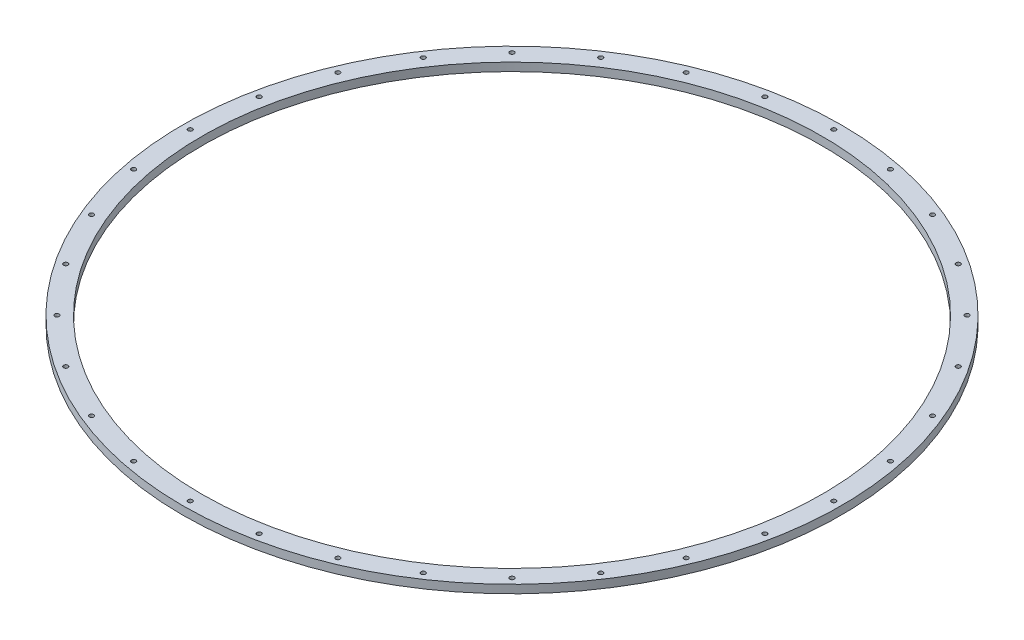
SolidWorks part; units mm, degrees
material "AISI 304"
ref_plane "Front" through (0, 0, 0) normal (0, 0, 1) x (1, 0, 0)
ref_plane "Top" through (0, 0, 0) normal (0, 1, 0) x (1, 0, 0)
ref_plane "Right" through (0, 0, 0) normal (1, 0, 0) x (0, 0, -1)
sketch "Sketch1" plane through (0, 0, 0) normal (0, 1, 0) x (1, 0, 0)
  circle A0 centre (0, 0) radius 239
  circle A1 centre (0, 0) radius 254
  dimension "D1" = 508
  dimension "D2" = 478
extrude "Boss-Extrude1" add sketch "Sketch1" along normal mid plane 6.35
hole_wizard "M3 Clearance Hole1" positions "Sketch2" profile "Sketch3" hole size "M3" standard "ANSI Metric" end condition up to next
sketch "Sketch2" plane through (0, 3.175, 0) normal (0, 1, 0) x (1, 0, 0)
  line L3 (-248, 0) -> (248, 0) construction
  point P0 (248, 0)
  point P6 (243.2347, -48.3824)
  point P7 (229.1221, -94.9055)
  point P8 (206.2045, -137.7814)
  point P9 (175.3625, -175.3625)
  point P10 (137.7814, -206.2045)
  point P11 (94.9055, -229.1221)
  point P12 (48.3824, -243.2347)
  point P13 (0, -248)
  point P14 (-48.3824, -243.2347)
  point P15 (-94.9055, -229.1221)
  point P16 (-137.7814, -206.2045)
  point P17 (-175.3625, -175.3625)
  point P18 (-206.2045, -137.7814)
  point P19 (-229.1221, -94.9055)
  point P20 (-243.2347, -48.3824)
  point P29 (-248, 0)
  point P30 (-243.2347, 48.3824)
  point P31 (-229.1221, 94.9055)
  point P32 (-206.2045, 137.7814)
  point P33 (-175.3625, 175.3625)
  point P34 (-137.7814, 206.2045)
  point P35 (-94.9055, 229.1221)
  point P36 (-48.3824, 243.2347)
  point P37 (0, 248)
  point P38 (48.3824, 243.2347)
  point P39 (94.9055, 229.1221)
  point P40 (137.7814, 206.2045)
  point P41 (175.3625, 175.3625)
  point P42 (206.2045, 137.7814)
  point P43 (229.1221, 94.9055)
  point P44 (243.2347, 48.3824)
  dimension "D2" = 248
  dimension "D1" = 32
sketch "Sketch3" plane through (248, 3.175, 0) normal (1, 0, 0) x (0, 0, 1)
  line L0 (0, 0) -> (0, 6.35)
  line L1 (0, 6.35) -> (1.7, 6.35)
  line L2 (1.7, 6.35) -> (1.7, 0)
  line L5 (1.7, 0) -> (0, 0)
  line L11 (0, -6.35) -> (0, 107.95) construction
  dimension "Thru Hole Dia." = 3.4
  dimension "Thru Hole Depth" = 6.35
